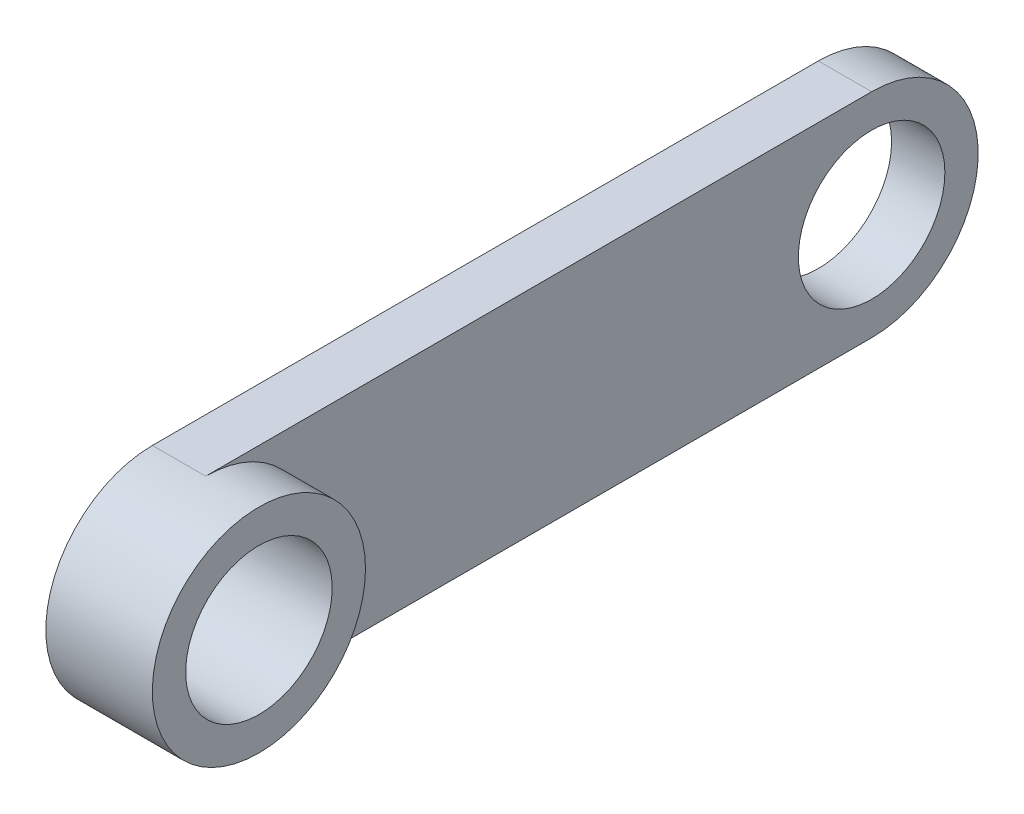
SolidWorks part; units mm, degrees
ref_plane "Front Plane" through (0, 0, 0) normal (0, 0, 1) x (1, 0, 0)
ref_plane "Top Plane" through (0, 0, 0) normal (0, 1, 0) x (1, 0, 0)
ref_plane "Right Plane" through (0, 0, 0) normal (1, 0, 0) x (0, 0, -1)
sketch "Sketch1" plane through (0, 0, 0) normal (1, 0, 0) x (0, 0, -1)
  line L0 (0, 4) -> (30, 4) construction
  line L1 (4, 0) -> (29, 0)
  line L3 (4, 8) -> (29, 8)
  circle A0 centre (4, 4) radius 2.75
  circle A1 centre (29, 4) radius 2.75
  arc A2 (4, 8) -> (4, 0) centre (4, 4) ccw
  arc A3 (29, 0) -> (29, 8) centre (29, 4) ccw
  dimension "D3" = 5.5
  dimension "D4" = 5.5
  dimension "D2" = 1.25
  dimension "D1" = 25
extrude "Boss-Extrude1" add sketch "Sketch1" along normal blind 2
sketch "Sketch2" plane through (0, 0, 0) normal (1, 0, 0) x (0, 0, -1)
  circle A0 centre (4, 4) radius 2.75
  circle A1 centre (4, 4) radius 4
extrude "Boss-Extrude2" add sketch "Sketch2" along normal blind 4
